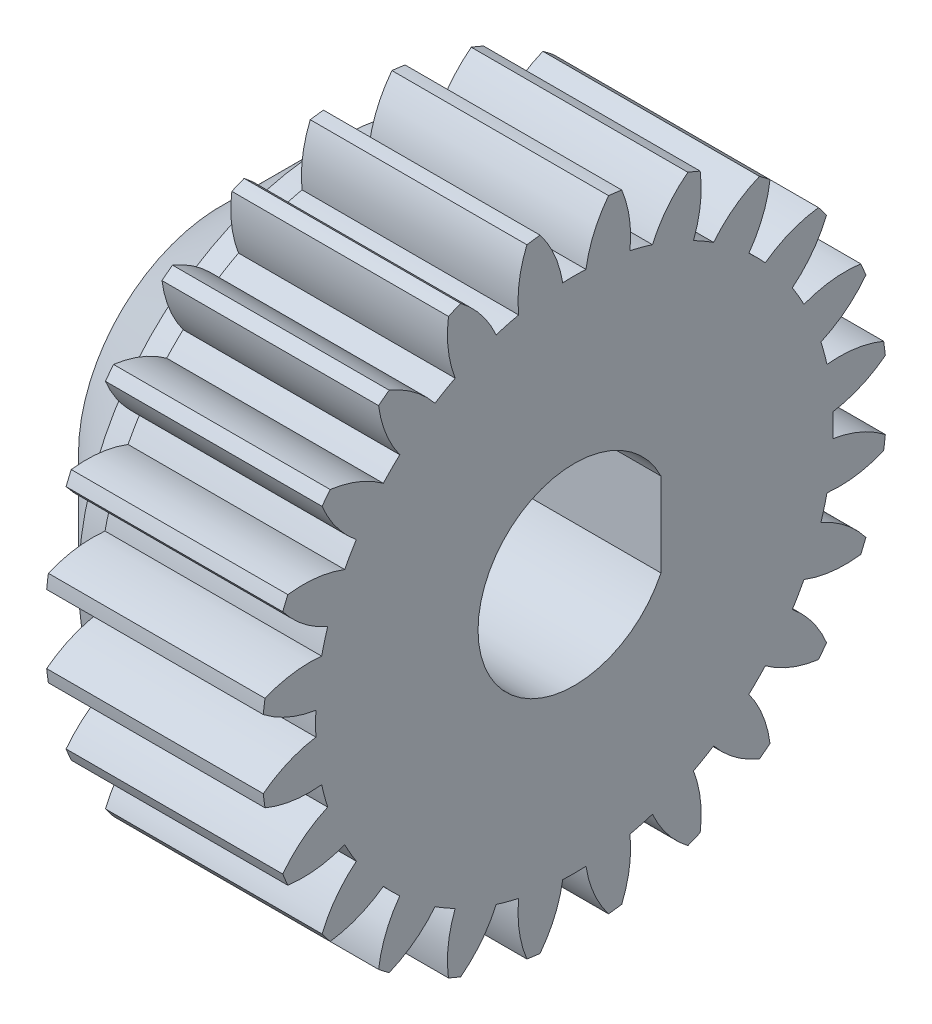
SolidWorks part; units mm, degrees
ref_plane "前视基准面" through (0, 0, 0) normal (0, 0, 1) x (1, 0, 0)
ref_plane "上视基准面" through (0, 0, 0) normal (0, 1, 0) x (1, 0, 0)
ref_plane "右视基准面" through (0, 0, 0) normal (1, 0, 0) x (0, 0, -1)
ref_plane "基准面4" through (0, 0, 0) normal (0, 0, -1) x (-1, 0, 0)
sketch "草图1" plane through (0, 0, 0) normal (0, 0, -1) x (-1, 0, 0)
  line L0 (-4.5, 6.5) -> (-4.5, 0)
  line L1 (-4.5, 0) -> (0, 0)
  line L2 (0, 0) -> (0, 6.5)
  line L3 (0, 6.5) -> (-4.5, 6.5)
  line L4 (-4.5, 0) -> (0, 0) construction
revolve "旋转1" add sketch "草图1" angle 360 about L4
sketch "草图2" plane through (4.5, 0, 0) normal (1, 0, 0) x (0, 0, -1)
  arc A0 (-6.0567, 2.3593) -> (-6.4249, 0.9851) centre (0, 0) ccw
  arc A1 (-6.4249, 0.9851) -> (-5.2482, 1.1561) centre (-5.5023, -1.2304) cw
  arc A2 (-5.2482, 1.1561) -> (-5.1231, 1.6229) centre (0, 0) cw
  arc A3 (-5.1231, 1.6229) -> (-6.0567, 2.3593) centre (-4.1499, 3.8167) cw
extrude "切除-拉伸1" cut sketch "草图2" against normal through all
sketch "草图3" plane through (4.5, 0, 0) normal (1, 0, 0) x (0, 0, -1)
  arc A0 (-5.2397, 3.8465) -> (-5.951, 2.6144) centre (0, 0) ccw
  arc A1 (-5.951, 2.6144) -> (-4.7701, 2.475) centre (-5.6332, 0.2356) cw
  arc A2 (-4.7701, 2.475) -> (-4.5285, 2.8936) centre (0, 0) cw
  arc A3 (-4.5285, 2.8936) -> (-5.2397, 3.8465) centre (-3.0206, 4.7607) cw
extrude "切除-拉伸2" cut sketch "草图3" against normal through all
sketch "草图4" plane through (4.5, 0, 0) normal (1, 0, 0) x (0, 0, -1)
  arc A0 (-4.0656, 5.0716) -> (-5.0716, 4.0656) centre (0, 0) ccw
  arc A1 (-5.0716, 4.0656) -> (-3.967, 3.6253) centre (-5.3803, 1.6855) cw
  arc A2 (-3.967, 3.6253) -> (-3.6253, 3.967) centre (0, 0) cw
  arc A3 (-3.6253, 3.967) -> (-4.0656, 5.0716) centre (-1.6855, 5.3803) cw
extrude "切除-拉伸3" cut sketch "草图4" against normal through all
sketch "草图5" plane through (4.5, 0, 0) normal (1, 0, 0) x (0, 0, -1)
  arc A0 (-3.8465, 5.2397) -> (-2.8936, 4.5285) centre (-4.7607, 3.0206) cw
  arc A1 (-2.8936, 4.5285) -> (-2.475, 4.7701) centre (0, 0) cw
  arc A2 (-2.475, 4.7701) -> (-2.6144, 5.951) centre (-0.2356, 5.6332) cw
  arc A3 (-2.6144, 5.951) -> (-3.8465, 5.2397) centre (0, 0) ccw
extrude "切除-拉伸4" cut sketch "草图5" against normal through all
sketch "草图6" plane through (4.5, 0, 0) normal (1, 0, 0) x (0, 0, -1)
  arc A0 (-2.3593, 6.0567) -> (-1.6229, 5.1231) centre (-3.8167, 4.1499) cw
  arc A1 (-1.6229, 5.1231) -> (-1.1561, 5.2482) centre (0, 0) cw
  arc A2 (-1.1561, 5.2482) -> (-0.9851, 6.4249) centre (1.2304, 5.5023) cw
  arc A3 (-0.9851, 6.4249) -> (-2.3593, 6.0567) centre (0, 0) ccw
extrude "切除-拉伸5" cut sketch "草图6" against normal through all
sketch "草图7" plane through (4.5, 0, 0) normal (1, 0, 0) x (0, 0, -1)
  arc A0 (0.7113, 6.461) -> (-0.7113, 6.461) centre (0, 0) ccw
  arc A1 (-0.7113, 6.461) -> (-0.2416, 5.3686) centre (-2.6126, 4.9963) cw
  arc A2 (-0.2416, 5.3686) -> (0.2416, 5.3686) centre (0, 0) cw
  arc A3 (0.2416, 5.3686) -> (0.7113, 6.461) centre (2.6126, 4.9963) cw
extrude "切除-拉伸6" cut sketch "草图7" against normal through all
sketch "草图8" plane through (4.5, 0, 0) normal (1, 0, 0) x (0, 0, -1)
  arc A0 (2.3593, 6.0567) -> (0.9851, 6.4249) centre (0, 0) ccw
  arc A1 (0.9851, 6.4249) -> (1.1561, 5.2482) centre (-1.2304, 5.5023) cw
  arc A2 (1.1561, 5.2482) -> (1.6229, 5.1231) centre (0, 0) cw
  arc A3 (1.6229, 5.1231) -> (2.3593, 6.0567) centre (3.8167, 4.1499) cw
extrude "切除-拉伸7" cut sketch "草图8" against normal through all
sketch "草图9" plane through (4.5, 0, 0) normal (1, 0, 0) x (0, 0, -1)
  arc A0 (3.8465, 5.2397) -> (2.6144, 5.951) centre (0, 0) ccw
  arc A1 (2.6144, 5.951) -> (2.475, 4.7701) centre (0.2356, 5.6332) cw
  arc A2 (2.475, 4.7701) -> (2.8936, 4.5285) centre (0, 0) cw
  arc A3 (2.8936, 4.5285) -> (3.8465, 5.2397) centre (4.7607, 3.0206) cw
extrude "切除-拉伸8" cut sketch "草图9" against normal through all
sketch "草图10" plane through (4.5, 0, 0) normal (1, 0, 0) x (0, 0, -1)
  arc A0 (5.0716, 4.0656) -> (4.0656, 5.0716) centre (0, 0) ccw
  arc A1 (4.0656, 5.0716) -> (3.6253, 3.967) centre (1.6855, 5.3803) cw
  arc A2 (3.6253, 3.967) -> (3.967, 3.6253) centre (0, 0) cw
  arc A3 (3.967, 3.6253) -> (5.0716, 4.0656) centre (5.3803, 1.6855) cw
extrude "切除-拉伸9" cut sketch "草图10" against normal through all
sketch "草图11" plane through (4.5, 0, 0) normal (1, 0, 0) x (0, 0, -1)
  arc A0 (5.951, 2.6144) -> (5.2397, 3.8465) centre (0, 0) ccw
  arc A1 (5.2397, 3.8465) -> (4.5285, 2.8936) centre (3.0206, 4.7607) cw
  arc A2 (4.5285, 2.8936) -> (4.7701, 2.475) centre (0, 0) cw
  arc A3 (4.7701, 2.475) -> (5.951, 2.6144) centre (5.6332, 0.2356) cw
extrude "切除-拉伸10" cut sketch "草图11" against normal through all
sketch "草图12" plane through (4.5, 0, 0) normal (1, 0, 0) x (0, 0, -1)
  arc A0 (6.4249, 0.9851) -> (6.0567, 2.3593) centre (0, 0) ccw
  arc A1 (6.0567, 2.3593) -> (5.1231, 1.6229) centre (4.1499, 3.8167) cw
  arc A2 (5.1231, 1.6229) -> (5.2482, 1.1561) centre (0, 0) cw
  arc A3 (5.2482, 1.1561) -> (6.4249, 0.9851) centre (5.5023, -1.2304) cw
extrude "切除-拉伸11" cut sketch "草图12" against normal through all
sketch "草图13" plane through (4.5, 0, 0) normal (1, 0, 0) x (0, 0, -1)
  arc A0 (6.461, -0.7113) -> (6.461, 0.7113) centre (0, 0) ccw
  arc A1 (6.461, 0.7113) -> (5.3686, 0.2416) centre (4.9963, 2.6126) cw
  arc A2 (5.3686, 0.2416) -> (5.3686, -0.2416) centre (0, 0) cw
  arc A3 (5.3686, -0.2416) -> (6.461, -0.7113) centre (4.9963, -2.6126) cw
extrude "切除-拉伸12" cut sketch "草图13" against normal through all
sketch "草图14" plane through (4.5, 0, 0) normal (1, 0, 0) x (0, 0, -1)
  arc A0 (6.0567, -2.3593) -> (6.4249, -0.9851) centre (0, 0) ccw
  arc A1 (6.4249, -0.9851) -> (5.2482, -1.1561) centre (5.5023, 1.2304) cw
  arc A2 (5.2482, -1.1561) -> (5.1231, -1.6229) centre (0, 0) cw
  arc A3 (5.1231, -1.6229) -> (6.0567, -2.3593) centre (4.1499, -3.8167) cw
extrude "切除-拉伸13" cut sketch "草图14" against normal through all
sketch "草图15" plane through (4.5, 0, 0) normal (1, 0, 0) x (0, 0, -1)
  arc A0 (5.2397, -3.8465) -> (5.951, -2.6144) centre (0, 0) ccw
  arc A1 (5.951, -2.6144) -> (4.7701, -2.475) centre (5.6332, -0.2356) cw
  arc A2 (4.7701, -2.475) -> (4.5285, -2.8936) centre (0, 0) cw
  arc A3 (4.5285, -2.8936) -> (5.2397, -3.8465) centre (3.0206, -4.7607) cw
extrude "切除-拉伸14" cut sketch "草图15" against normal through all
sketch "草图16" plane through (4.5, 0, 0) normal (1, 0, 0) x (0, 0, -1)
  arc A0 (4.0656, -5.0716) -> (5.0716, -4.0656) centre (0, 0) ccw
  arc A1 (5.0716, -4.0656) -> (3.967, -3.6253) centre (5.3803, -1.6855) cw
  arc A2 (3.967, -3.6253) -> (3.6253, -3.967) centre (0, 0) cw
  arc A3 (3.6253, -3.967) -> (4.0656, -5.0716) centre (1.6855, -5.3803) cw
extrude "切除-拉伸15" cut sketch "草图16" against normal through all
sketch "草图17" plane through (4.5, 0, 0) normal (1, 0, 0) x (0, 0, -1)
  arc A0 (2.6144, -5.951) -> (3.8465, -5.2397) centre (0, 0) ccw
  arc A1 (3.8465, -5.2397) -> (2.8936, -4.5285) centre (4.7607, -3.0206) cw
  arc A2 (2.8936, -4.5285) -> (2.475, -4.7701) centre (0, 0) cw
  arc A3 (2.475, -4.7701) -> (2.6144, -5.951) centre (0.2356, -5.6332) cw
extrude "切除-拉伸16" cut sketch "草图17" against normal through all
sketch "草图18" plane through (4.5, 0, 0) normal (1, 0, 0) x (0, 0, -1)
  arc A0 (0.9851, -6.4249) -> (2.3593, -6.0567) centre (0, 0) ccw
  arc A1 (2.3593, -6.0567) -> (1.6229, -5.1231) centre (3.8167, -4.1499) cw
  arc A2 (1.6229, -5.1231) -> (1.1561, -5.2482) centre (0, 0) cw
  arc A3 (1.1561, -5.2482) -> (0.9851, -6.4249) centre (-1.2304, -5.5023) cw
extrude "切除-拉伸17" cut sketch "草图18" against normal through all
sketch "草图19" plane through (4.5, 0, 0) normal (1, 0, 0) x (0, 0, -1)
  arc A0 (-0.7113, -6.461) -> (0.7113, -6.461) centre (0, 0) ccw
  arc A1 (0.7113, -6.461) -> (0.2416, -5.3686) centre (2.6126, -4.9963) cw
  arc A2 (0.2416, -5.3686) -> (-0.2416, -5.3686) centre (0, 0) cw
  arc A3 (-0.2416, -5.3686) -> (-0.7113, -6.461) centre (-2.6126, -4.9963) cw
extrude "切除-拉伸18" cut sketch "草图19" against normal through all
sketch "草图20" plane through (4.5, 0, 0) normal (1, 0, 0) x (0, 0, -1)
  arc A0 (-2.3593, -6.0567) -> (-0.9851, -6.4249) centre (0, 0) ccw
  arc A1 (-0.9851, -6.4249) -> (-1.1561, -5.2482) centre (1.2304, -5.5023) cw
  arc A2 (-1.1561, -5.2482) -> (-1.6229, -5.1231) centre (0, 0) cw
  arc A3 (-1.6229, -5.1231) -> (-2.3593, -6.0567) centre (-3.8167, -4.1499) cw
extrude "切除-拉伸19" cut sketch "草图20" against normal through all
sketch "草图21" plane through (4.5, 0, 0) normal (1, 0, 0) x (0, 0, -1)
  arc A0 (-3.8465, -5.2397) -> (-2.6144, -5.951) centre (0, 0) ccw
  arc A1 (-2.6144, -5.951) -> (-2.475, -4.7701) centre (-0.2356, -5.6332) cw
  arc A2 (-2.475, -4.7701) -> (-2.8936, -4.5285) centre (0, 0) cw
  arc A3 (-2.8936, -4.5285) -> (-3.8465, -5.2397) centre (-4.7607, -3.0206) cw
extrude "切除-拉伸20" cut sketch "草图21" against normal through all
sketch "草图22" plane through (4.5, 0, 0) normal (1, 0, 0) x (0, 0, -1)
  arc A0 (-5.0716, -4.0656) -> (-4.0656, -5.0716) centre (0, 0) ccw
  arc A1 (-4.0656, -5.0716) -> (-3.6253, -3.967) centre (-1.6855, -5.3803) cw
  arc A2 (-3.6253, -3.967) -> (-3.967, -3.6253) centre (0, 0) cw
  arc A3 (-3.967, -3.6253) -> (-5.0716, -4.0656) centre (-5.3803, -1.6855) cw
extrude "切除-拉伸21" cut sketch "草图22" against normal through all
sketch "草图23" plane through (4.5, 0, 0) normal (1, 0, 0) x (0, 0, -1)
  arc A0 (-5.951, -2.6144) -> (-5.2397, -3.8465) centre (0, 0) ccw
  arc A1 (-5.2397, -3.8465) -> (-4.5285, -2.8936) centre (-3.0206, -4.7607) cw
  arc A2 (-4.5285, -2.8936) -> (-4.7701, -2.475) centre (0, 0) cw
  arc A3 (-4.7701, -2.475) -> (-5.951, -2.6144) centre (-5.6332, -0.2356) cw
extrude "切除-拉伸22" cut sketch "草图23" against normal through all
sketch "草图24" plane through (4.5, 0, 0) normal (1, 0, 0) x (0, 0, -1)
  arc A0 (-6.4249, -0.9851) -> (-6.0567, -2.3593) centre (0, 0) ccw
  arc A1 (-6.0567, -2.3593) -> (-5.1231, -1.6229) centre (-4.1499, -3.8167) cw
  arc A2 (-5.1231, -1.6229) -> (-5.2482, -1.1561) centre (0, 0) cw
  arc A3 (-5.2482, -1.1561) -> (-6.4249, -0.9851) centre (-5.5023, 1.2304) cw
extrude "切除-拉伸23" cut sketch "草图24" against normal through all
sketch "草图25" plane through (4.5, 0, 0) normal (1, 0, 0) x (0, 0, -1)
  arc A0 (-6.461, 0.7113) -> (-6.461, -0.7113) centre (0, 0) ccw
  arc A1 (-6.461, -0.7113) -> (-5.3686, -0.2416) centre (-4.9963, -2.6126) cw
  arc A2 (-5.3686, -0.2416) -> (-5.3686, 0.2416) centre (0, 0) cw
  arc A3 (-5.3686, 0.2416) -> (-6.461, 0.7113) centre (-4.9963, 2.6126) cw
extrude "切除-拉伸24" cut sketch "草图25" against normal through all
sketch "草图28" plane through (0, 0, 0) normal (-1, 0, 0) x (0, 0, 1)
  circle A0 centre (0, 0) radius 5.3
extrude "凸台-拉伸2" add sketch "草图28" along normal blind 0.5
sketch "草图26" plane through (-0.5, 0, 0) normal (-1, 0, 0) x (0, 0, 1)
  circle A0 centre (0, 0) radius 5.3
extrude "凸台-拉伸1" add sketch "草图26" along normal blind 2.33 draft 45
sketch "草图27" plane through (4.5, 0, 0) normal (1, 0, 0) x (0, 0, -1)
  line L0 (1.8, -0.8718) -> (1.8, 0.8718)
  arc A0 (1.8, 0.8718) -> (1.8, -0.8718) centre (0, 0) ccw
  dimension "D1" = 2
  dimension "D2" = 1.8
extrude "切除-拉伸25" cut sketch "草图27" against normal through all
